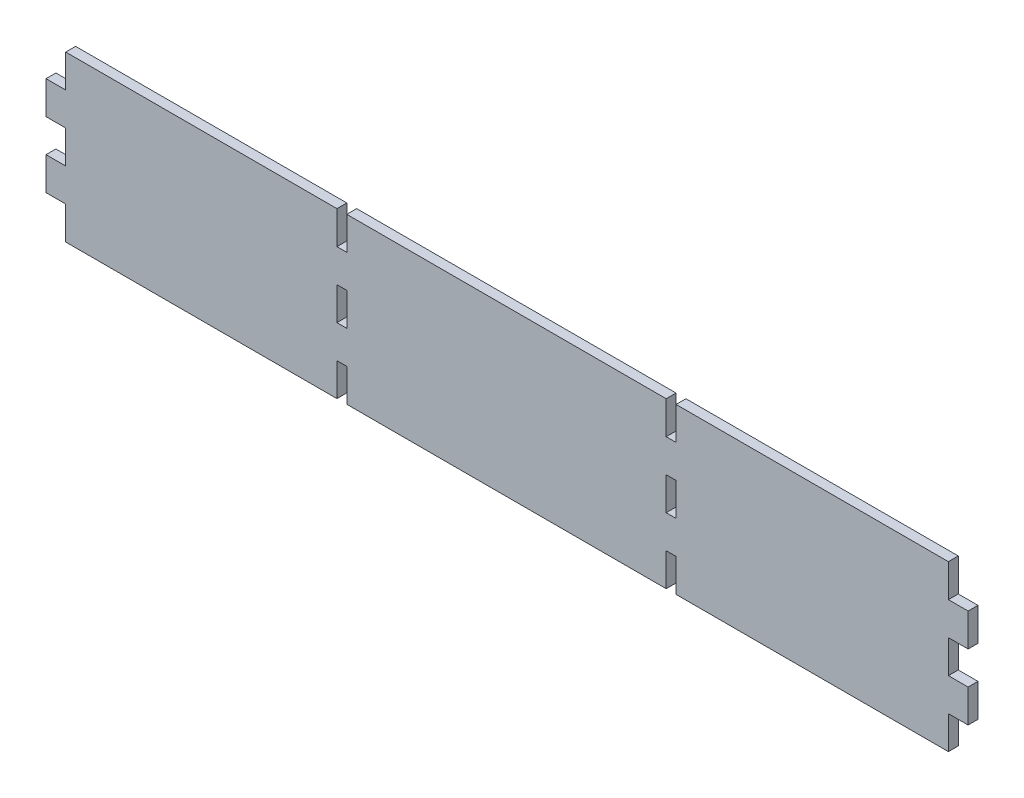
SolidWorks part; units mm, degrees
material "Pine"
ref_plane "Front Plane" through (0, 0, 0) normal (0, 0, 1) x (1, 0, 0)
ref_plane "Top Plane" through (0, 0, 0) normal (0, 1, 0) x (1, 0, 0)
ref_plane "Right Plane" through (0, 0, 0) normal (1, 0, 0) x (0, 0, -1)
sketch "Sketch1" plane through (0, 0, 0) normal (0, 0, 1) x (1, 0, 0)
  line L33 (-85.4, 23.2) -> (-91.4, 23.2) construction
  line L34 (-91.4, 23.2) -> (-91.4, 13.2) construction
  line L35 (-91.4, 13.2) -> (-85.4, 13.2) construction
  line L37 (-85.4, 43.2) -> (-91.4, 43.2) construction
  line L38 (-91.4, 43.2) -> (-91.4, 33.2) construction
  line L39 (-91.4, 33.2) -> (-85.4, 33.2) construction
  line L41 (-85.4, 23.2) -> (-91.4, 23.2)
  line L42 (-91.4, 23.2) -> (-91.4, 13.2)
  line L43 (-91.4, 13.2) -> (-85.4, 13.2)
  line L45 (-85.4, 43.2) -> (-91.4, 43.2)
  line L46 (-91.4, 43.2) -> (-91.4, 33.2)
  line L47 (-91.4, 33.2) -> (-85.4, 33.2)
  line L48 (188.8, 33.2) -> (188.8, 43.2) construction
  line L49 (188.8, 43.2) -> (182.8, 43.2) construction
  line L51 (182.8, 33.2) -> (188.8, 33.2) construction
  line L52 (188.8, 13.2) -> (188.8, 23.2) construction
  line L53 (188.8, 23.2) -> (182.8, 23.2) construction
  line L55 (182.8, 13.2) -> (188.8, 13.2) construction
  line L56 (188.8, 33.2) -> (188.8, 43.2)
  line L57 (188.8, 43.2) -> (182.8, 43.2)
  line L59 (182.8, 33.2) -> (188.8, 33.2)
  line L60 (188.8, 13.2) -> (188.8, 23.2)
  line L61 (188.8, 23.2) -> (182.8, 23.2)
  line L63 (182.8, 13.2) -> (188.8, 13.2)
  line L64 (182.8, 77.6252) -> (182.8, 44.551) construction
  line L65 (-85.4, 3.2) -> (-3, 3.2)
  line L66 (-85.4, 3.2) -> (-85.4, 13.2)
  line L67 (-85.4, 53.2) -> (-3, 53.2)
  line L68 (182.8, 3.2) -> (182.8, 13.2)
  line L69 (97.05, 53.2) -> (100.05, 53.2) construction
  line L70 (100.05, 23.2) -> (100.05, 33.2) construction
  line L71 (100.05, 33.2) -> (97.05, 33.2) construction
  line L72 (97.05, 33.2) -> (97.05, 23.2) construction
  line L73 (97.05, 23.2) -> (100.05, 23.2) construction
  line L74 (100.05, 43.2) -> (100.05, 53.2) construction
  line L76 (97.05, 53.2) -> (97.05, 43.2) construction
  line L77 (97.05, 43.2) -> (100.05, 43.2) construction
  line L78 (100.05, 3.2) -> (100.05, 13.2) construction
  line L79 (100.05, 13.2) -> (97.05, 13.2) construction
  line L80 (97.05, 13.2) -> (97.05, 3.2) construction
  line L82 (0, 3.2) -> (0, 13.2) construction
  line L83 (0, 13.2) -> (-3, 13.2) construction
  line L84 (-3, 13.2) -> (-3, 3.2) construction
  line L86 (0, 23.2) -> (0, 33.2) construction
  line L87 (0, 33.2) -> (-3, 33.2) construction
  line L88 (-3, 33.2) -> (-3, 23.2) construction
  line L89 (-3, 23.2) -> (0, 23.2) construction
  line L90 (0, 43.2) -> (0, 53.2) construction
  line L92 (-3, 53.2) -> (-3, 43.2) construction
  line L93 (-3, 43.2) -> (0, 43.2) construction
  line L94 (100.05, 23.2) -> (100.05, 33.2)
  line L95 (100.05, 33.2) -> (97.05, 33.2)
  line L96 (97.05, 33.2) -> (97.05, 23.2)
  line L97 (97.05, 23.2) -> (100.05, 23.2)
  line L98 (100.05, 43.2) -> (100.05, 53.2)
  line L100 (97.05, 53.2) -> (97.05, 43.2)
  line L101 (97.05, 43.2) -> (100.05, 43.2)
  line L102 (100.05, 3.2) -> (100.05, 13.2)
  line L103 (100.05, 13.2) -> (97.05, 13.2)
  line L104 (97.05, 13.2) -> (97.05, 3.2)
  line L106 (0, 3.2) -> (0, 13.2)
  line L107 (0, 13.2) -> (-3, 13.2)
  line L108 (-3, 13.2) -> (-3, 3.2)
  line L110 (0, 23.2) -> (0, 33.2)
  line L111 (0, 33.2) -> (-3, 33.2)
  line L112 (-3, 33.2) -> (-3, 23.2)
  line L113 (-3, 23.2) -> (0, 23.2)
  line L114 (0, 43.2) -> (0, 53.2)
  line L116 (-3, 53.2) -> (-3, 43.2)
  line L117 (-3, 43.2) -> (0, 43.2)
  line L118 (0, 53.2) -> (97.05, 53.2)
  line L119 (100.05, 53.2) -> (182.8, 53.2)
  line L120 (100.05, 3.2) -> (182.8, 3.2)
  line L121 (0, 3.2) -> (97.05, 3.2)
  line L122 (182.8, 23.2) -> (182.8, 33.2)
  line L123 (182.8, 43.2) -> (182.8, 53.2)
  line L124 (-85.4, 43.2) -> (-85.4, 53.2)
  line L125 (-85.4, 23.2) -> (-85.4, 33.2)
extrude "Boss-Extrude1" add sketch "Sketch1" along normal blind 3
